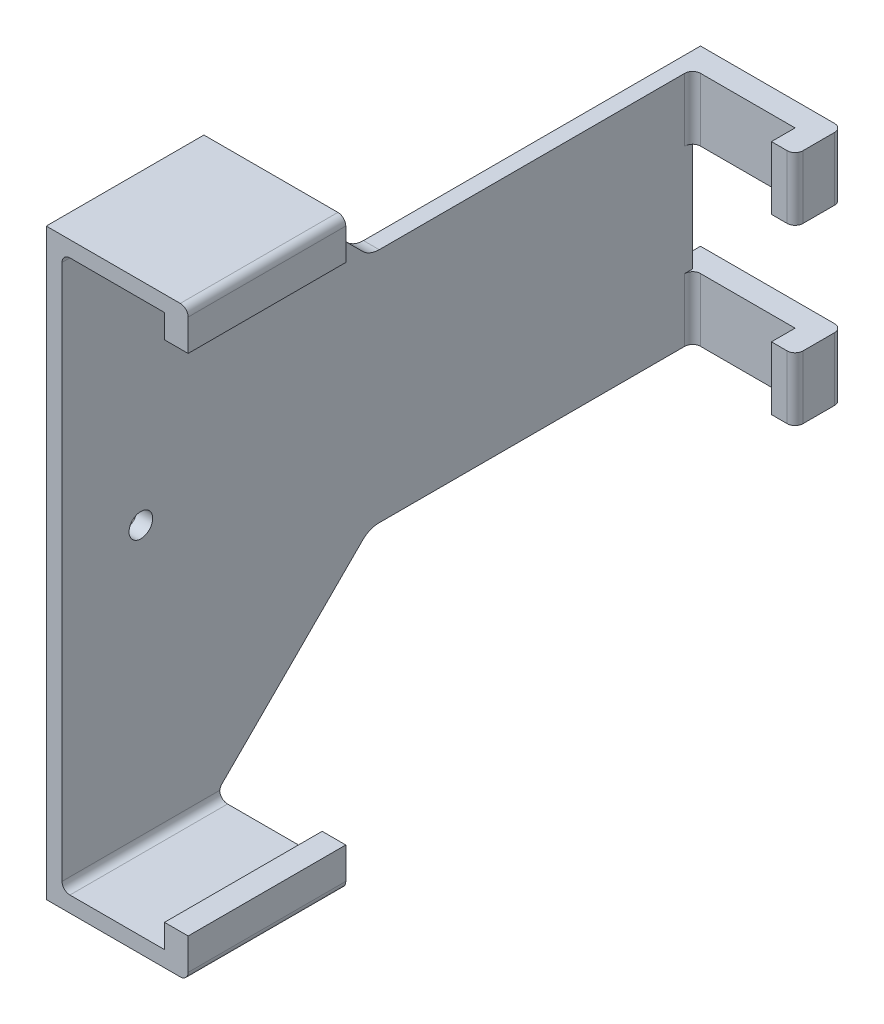
SolidWorks part; units mm, degrees
ref_plane "Front Plane" through (0, 0, 0) normal (0, 0, 1) x (1, 0, 0)
ref_plane "Top Plane" through (0, 0, 0) normal (0, 1, 0) x (1, 0, 0)
ref_plane "Right Plane" through (0, 0, 0) normal (1, 0, 0) x (0, 0, -1)
sketch "Esboço1" plane through (0, 0, 0) normal (0, 0, 1) x (1, 0, 0)
  line L0 (-4.2058, -35.2805) -> (-4.2058, 34.7195)
  line L1 (-4.2058, 34.7195) -> (8.7942, 34.7195)
  line L2 (8.7942, 34.7195) -> (8.7942, 31.7195)
  line L3 (-4.2058, -35.2805) -> (8.7942, -35.2805)
  line L4 (8.7942, 31.7195) -> (11.7942, 31.7195)
  line L5 (11.7942, 31.7195) -> (11.7942, 36.7195)
  line L6 (11.7942, 36.7195) -> (-6.2058, 36.7195)
  line L7 (-6.2058, 36.7195) -> (-6.2058, -37.2805)
  line L8 (-6.2058, -37.2805) -> (11.7942, -37.2805)
  line L10 (8.7942, -35.2805) -> (8.7942, -32.2805)
  line L11 (8.7942, -32.2805) -> (11.7942, -32.2805)
  line L12 (11.7942, -32.2805) -> (11.7942, -37.2805)
  dimension "D1" = 70
  dimension "D2" = 13
  dimension "D3" = 3
  dimension "D4" = 3
  dimension "D5" = 3
  dimension "D6" = 2
  dimension "D7" = 2
  dimension "D8" = 2
  dimension "D9" = 3
extrude "Ressalto-extrusão1" add sketch "Esboço1" along normal blind 20
sketch "Esboço2" plane through (0, 0, 0) normal (0, 0, -1) x (-1, 0, 0)
  line L0 (4.2058, -15) -> (4.2058, 15)
  line L1 (4.2058, -35.2805) -> (4.2058, 34.7195) construction
  line L2 (4.2058, 15) -> (6.2058, 15)
  line L3 (6.2058, 36.7195) -> (6.2058, -37.2805) construction
  line L4 (6.2058, 15) -> (6.2058, -15)
  line L5 (6.2058, -15) -> (4.2058, -15)
  point P4 (4.2058, 0)
  dimension "D1" = 30
extrude "Ressalto-extrusão2" add sketch "Esboço2" along normal blind 60
sketch "Esboço3" plane through (0, 15, 0) normal (0, 1, 0) x (1, 0, 0)
  line L0 (-6.2058, 60) -> (-6.2058, 63)
  line L1 (-6.2058, 63) -> (11.7942, 63)
  line L2 (11.7942, 63) -> (11.7942, 57)
  line L3 (11.7942, 57) -> (8.7942, 57)
  line L4 (8.7942, 57) -> (8.7942, 60)
  line L5 (-6.2058, 60) -> (8.7942, 60)
  line L7 (11.7942, -20) -> (11.7942, 0) construction
  dimension "D1" = 3
  dimension "D2" = 3
  dimension "D3" = 3
extrude "Ressalto-extrusão3" add sketch "Esboço3" against normal blind 8
mirror "Espelhar1" about plane through (0, 0, 0) normal (0, 1, 0) of "Ressalto-extrusão3"
fillet "Filete1" radius 1 10 edges at (-4.2058, -35.2805, 10) (-4.2058, 34.7195, 10) (11.7942, 36.7195, 10) (11.7942, -37.2805, 10) (11.7942, 11, -57) (11.7942, -11, -57) (11.7942, -11, -63) (11.7942, 11, -63) (-4.2058, 11, -60) (-4.2058, -11, -60)
sketch "Esboço4" plane through (-4.2058, 0, 0) normal (1, 0, 0) x (0, 0, -1)
  line L0 (0, 0) -> (-20, -0.2805) construction
  line L1 (-20, -34.2805) -> (-20, 33.7195) construction
  circle A0 centre (-10, -0.1402) radius 1.5
  dimension "D1" = 3
extrude "Corte-extrusão1" cut sketch "Esboço4" against normal blind 8
chamfer "Chanfro1" distance 19 angle 45 2 edges at (-5.2058, -15, 0) (-5.2058, 15, 0)
fillet "Filete2" radius 3 2 edges at (-5.2058, -15, -19) (-5.2058, 15, -19)
fillet "Filete3" radius 1 2 edges at (-5.2058, -34, 0) (-5.1857, 34, 0)
